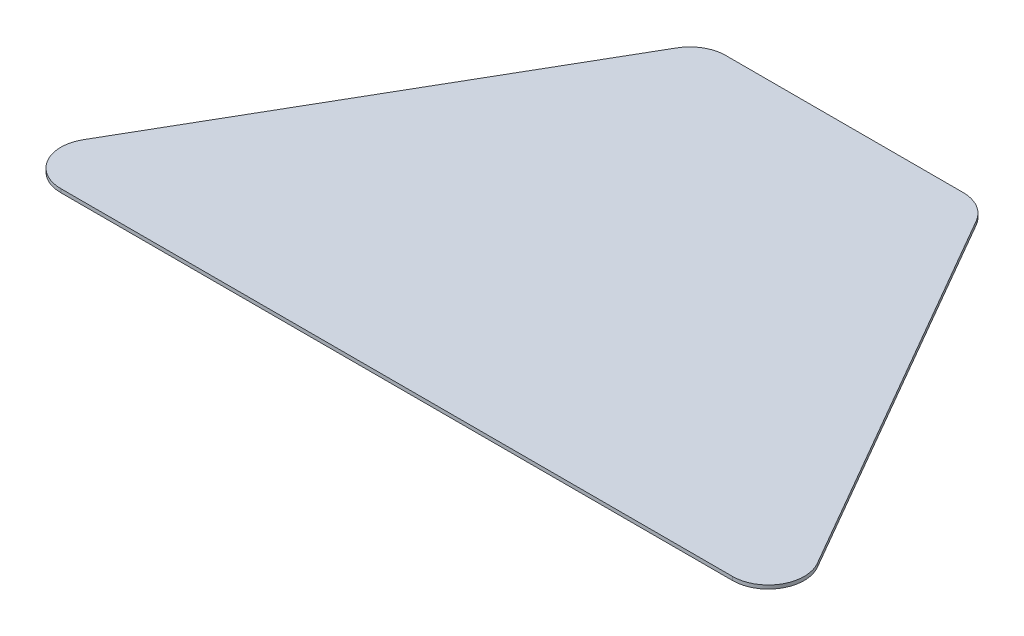
SolidWorks part; units mm, degrees
material "STYCAST 2850FT/Catalyst 23LV"
ref_plane "Front Plane" through (0, 0, 0) normal (0, 0, 1) x (1, 0, 0)
ref_plane "Top Plane" through (0, 0, 0) normal (0, 1, 0) x (1, 0, 0)
ref_plane "Right Plane" through (0, 0, 0) normal (1, 0, 0) x (0, 0, -1)
sketch "Sketch1" plane through (0, 0, 0) normal (0, 1, 0) x (1, 0, 0)
  line L1 (-14.2978, -12.5) -> (14.2978, -12.5)
  line L2 (-14.2978, -12.5) -> (-14.2978, 12.5) construction
  line L3 (-14.2978, 12.5) -> (14.2978, 12.5) construction
  line L4 (14.2978, -12.5) -> (14.2978, 12.5) construction
  line L5 (-14.2978, -12.5) -> (14.2978, 12.5) construction
  line L6 (-14.2978, 12.5) -> (14.2978, -12.5) construction
  line L8 (-7.7831, 12.5) -> (7.7831, 12.5)
  line L11 (0, 11.2271) -> (0, -49988.7729) construction
  line L14 (-7.7831, 12.5) -> (-22.2169, -12.5)
  line L15 (-22.2169, -12.5) -> (-14.2978, -12.5)
  line L16 (7.7831, 12.5) -> (22.2169, -12.5)
  line L17 (22.2169, -12.5) -> (14.2978, -12.5)
  line L24 (15, 0) -> (-15, 0) construction
  point P0 (0, 0)
  point P14 (0, 12.5)
  dimension "D1" = 25
  dimension "D2" = 30
  dimension "D4" = 60
extrude "Boss-Extrude1" add sketch "Sketch1" along normal mid plane 0.2
fillet "Fillet5" radius 2 4 edges at (22.2169, 0, 12.5) (-22.2169, 0, 12.5) (-7.7831, 0, -12.5) (7.7831, 0, -12.5)
equation "\"panel_width\"= 5.5in"
equation "\"finger_joint_width\"= 30mm"
